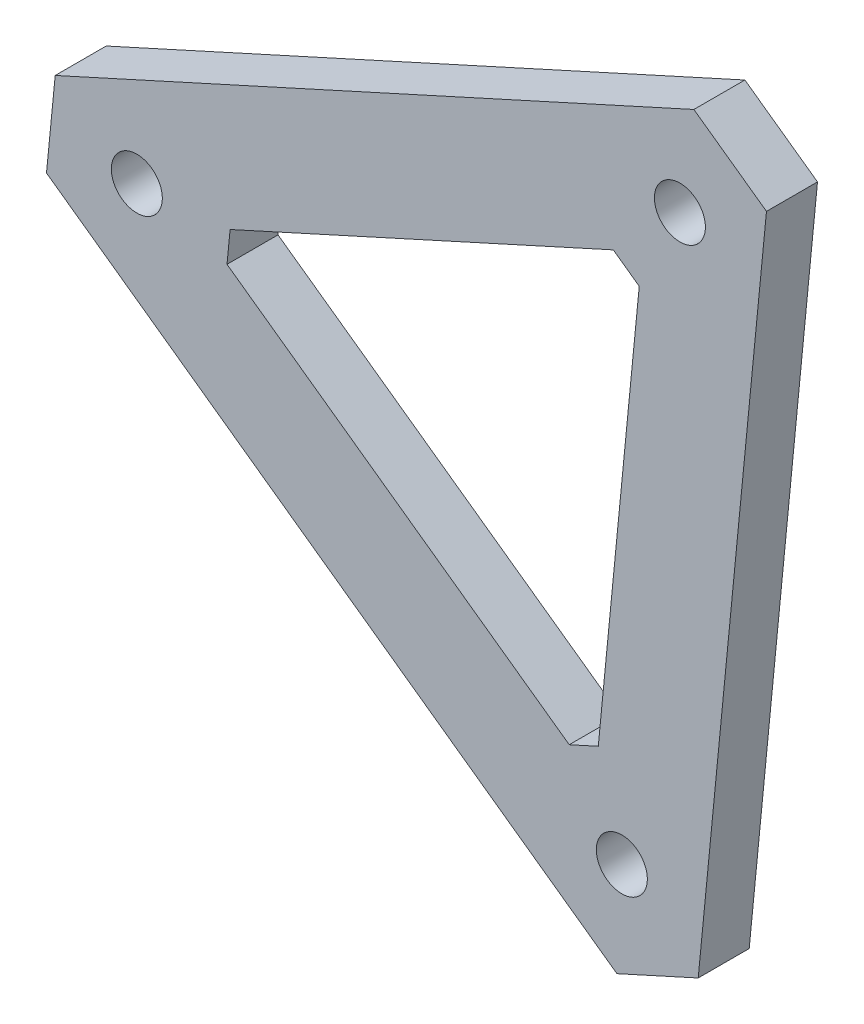
SolidWorks part; units mm, degrees
ref_plane "Front" through (0, 0, 0) normal (0, 0, 1) x (1, 0, 0)
ref_plane "Top" through (0, 0, 0) normal (0, 1, 0) x (1, 0, 0)
ref_plane "Right" through (0, 0, 0) normal (1, 0, 0) x (0, 0, -1)
sketch "Sketch1" plane through (0, 0, 0) normal (0, 0, 1) x (1, 0, 0)
  line L0 (-44.9806, -17.9308) -> (239.0402, -221.1738)
  line L1 (279.516, -202.8023) -> (313.5192, 144.7885)
  line L2 (277.3711, 170.6558) -> (-40.653, 26.308)
  line L3 (44.8927, -12.367) -> (215.3053, -134.3128)
  line L4 (229.7609, -127.7516) -> (250.1628, 80.8029)
  line L5 (237.2528, 90.0412) -> (46.4383, 3.4325)
  line L6 (-42.8168, 4.1886) -> (170.6355, -16.6925) construction
  line L7 (170.6355, -16.6925) -> (295.4451, 157.7221) construction
  line L8 (170.6355, -16.6925) -> (259.2781, -211.9881) construction
  line L9 (250.1628, 80.8029) -> (237.2528, 90.0412)
  line L10 (46.4383, 3.4325) -> (44.8927, -12.367)
  line L11 (215.3053, -134.3128) -> (229.7609, -127.7516)
  line L12 (277.3711, 170.6558) -> (313.5192, 144.7885)
  line L13 (-40.653, 26.308) -> (-44.9806, -17.9308)
  line L14 (239.0402, -221.1738) -> (279.516, -202.8023)
  circle A2 centre (0, 0) radius 12.7
  circle A4 centre (270.4093, 122.736) radius 12.7
  circle A5 centre (241.4971, -172.8134) radius 12.7
  point P3 (31.9827, -3.1287)
  point P4 (228.2153, -143.5512)
  point P5 (251.7084, 96.6025)
  point P9 (222.5331, -131.0322)
  point P10 (243.7078, 85.4221)
  point P11 (45.6655, -4.4672)
  dimension "D3" = 349.25
  dimension "D1" = 44.45
  dimension "D2" = 209.55
extrude "Extrude1" add sketch "Sketch1" against normal blind 25.4
